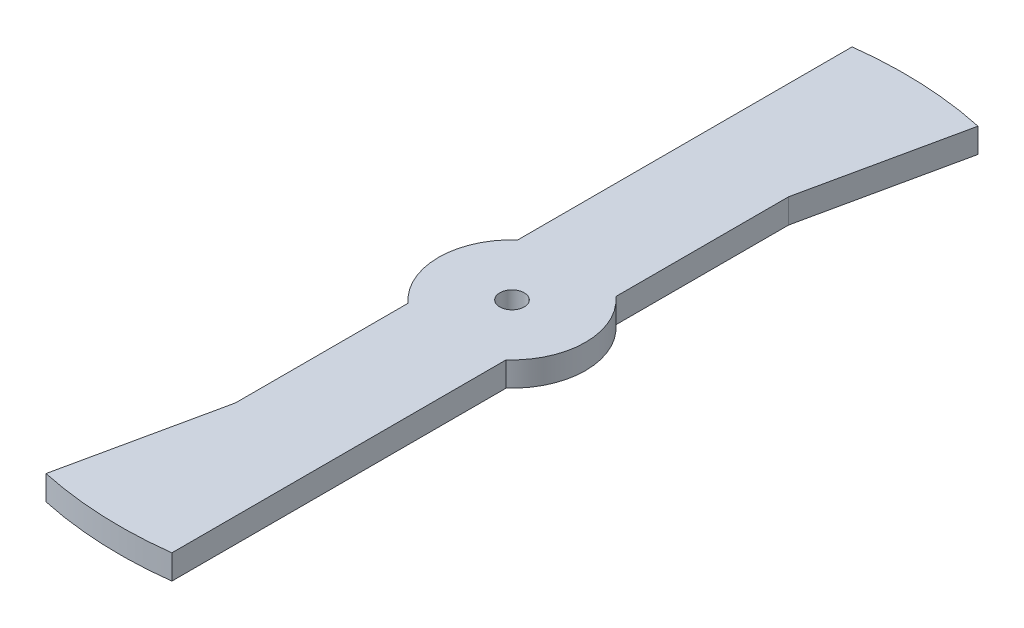
SolidWorks part; units mm, degrees
material "AISI 316 Stainless Steel Sheet (SS)"
ref_plane "Front Plane" through (0, 0, 0) normal (0, 0, 1) x (1, 0, 0)
ref_plane "Top Plane" through (0, 0, 0) normal (0, 1, 0) x (1, 0, 0)
ref_plane "Right Plane" through (0, 0, 0) normal (1, 0, 0) x (0, 0, -1)
sketch "Sketch1" plane through (0, 0, 0) normal (0, 1, 0) x (1, 0, 0)
  line L0 (0, 19.05) -> (0, 101.6) construction
  line L1 (-12.7, 100.8031) -> (-12.7, 14.199)
  line L2 (12.7, 14.199) -> (12.7, 58.973)
  line L3 (12.7, 58.973) -> (21.3895, 99.323)
  line L4 (12.7, -100.8031) -> (12.7, -14.199)
  line L5 (-12.7, -58.973) -> (-21.3895, -99.323)
  line L6 (-12.7, -14.199) -> (-12.7, -58.973)
  circle A0 centre (0, 0) radius 3.175
  circle A1 centre (0, 0) radius 19.05 construction
  circle A2 centre (0, 0) radius 101.6 construction
  arc A3 (-12.7, 100.8031) -> (21.3895, 99.323) centre (0, 0) cw
  circle A4 centre (0, 0) radius 60.325 construction
  arc A5 (12.7, -100.8031) -> (-21.3895, -99.323) centre (0, 0) cw
  arc A6 (-12.7, 14.199) -> (-12.7, -14.199) centre (0, 0) ccw
  arc A7 (12.7, 14.199) -> (12.7, -14.199) centre (0, 0) cw
  point P9 (12.7, 14.199)
  point P15 (0, 60.325)
  point P23 (0, 0)
  dimension "D1" = 6.35
  dimension "D2" = 38.1
  dimension "D3" = 203.2
  dimension "D4" = 25.4
  dimension "D6" = 2
extrude "Boss-Extrude1" add sketch "Sketch1" along normal blind 6.35 contours A7 L2 L3 A3 L1 A6 L6 L5 A5 L4 A0
